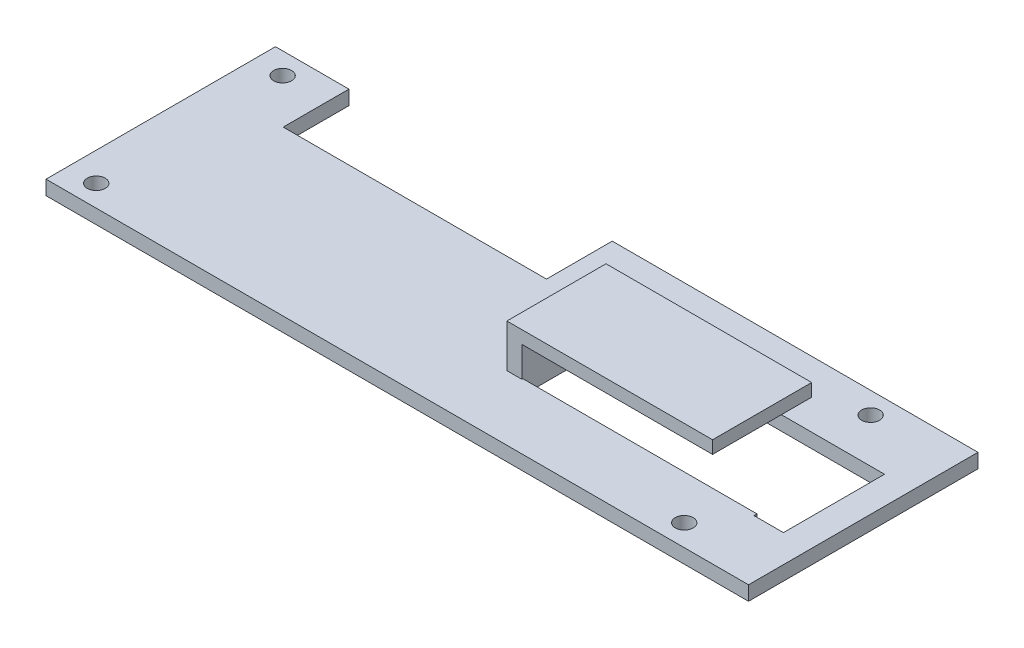
SolidWorks part; units mm, degrees
ref_plane "Front Plane" through (0, 0, 0) normal (0, 0, 1) x (1, 0, 0)
ref_plane "Top Plane" through (0, 0, 0) normal (0, 1, 0) x (1, 0, 0)
ref_plane "Right Plane" through (0, 0, 0) normal (1, 0, 0) x (0, 0, -1)
sketch "Sketch1" plane through (0, 0, 0) normal (0, 1, 0) x (1, 0, 0)
  line L1 (-57.15, -20.32) -> (57.15, -20.32)
  line L2 (-57.15, -20.32) -> (-57.15, 20.32)
  line L3 (-57.15, 20.32) -> (57.15, 20.32)
  line L4 (57.15, -20.32) -> (57.15, 20.32)
  line L5 (-57.15, -20.32) -> (57.15, 20.32) construction
  line L6 (-57.15, 20.32) -> (57.15, -20.32) construction
  point P0 (0, 0)
  dimension "D1" = 114.3
  dimension "D2" = 40.64
extrude "Boss-Extrude1" add sketch "Sketch1" along normal blind 2.54
sketch "Sketch2" plane through (0, 2.54, 0) normal (0, 1, 0) x (1, 0, 0)
  line L0 (57.15, 20.32) -> (-57.15, 20.32) construction
  line L1 (-57.15, -20.32) -> (57.15, -20.32) construction
  line L2 (-57.15, 20.32) -> (-57.15, -20.32) construction
  line L3 (57.15, -20.32) -> (57.15, 20.32) construction
  circle A0 centre (-52.07, 16.51) radius 1.5875
  circle A1 centre (52.07, 16.51) radius 1.5875
  circle A2 centre (52.07, -16.51) radius 1.5875
  circle A3 centre (-52.07, -16.51) radius 1.5875
  dimension "D1" = 3.175
  dimension "D2" = 3.81
  dimension "D3" = 3.81
  dimension "D4" = 3.81
  dimension "D5" = 3.81
  dimension "D6" = 5.08
  dimension "D7" = 5.08
  dimension "D8" = 5.08
  dimension "D9" = 5.08
extrude "Cut-Extrude2" cut sketch "Sketch2" against normal through all
sketch "Sketch3" plane through (0, 2.54, 0) normal (0, 1, 0) x (1, 0, 0)
  line L0 (57.15, 31.0755) -> (-57.15, 31.0755) construction
  line L1 (15.6834, -8.7) -> (58.8854, -8.7)
  line L2 (15.6834, -8.7) -> (15.6834, 8.6735)
  line L3 (15.6834, 8.6735) -> (58.8854, 8.6735)
  line L4 (58.8854, -8.7) -> (58.8854, 8.6735)
  line L5 (-44.1328, 8.6735) -> (2.4958, 8.6735)
  line L6 (-44.1328, 8.6735) -> (-44.1328, 31.0755)
  line L7 (-44.1328, 31.0755) -> (2.4958, 31.0755)
  line L8 (2.4958, 8.6735) -> (2.4958, 31.0755)
extrude "Cut-Extrude3" cut sketch "Sketch3" against normal through all
sketch "Sketch4" plane through (0, 2.54, 0) normal (0, 1, 0) x (1, 0, 0)
  line L1 (15.6834, 8.6735) -> (13.0397, 8.6735)
  line L2 (15.6834, 8.6735) -> (15.6834, -8.88)
  line L3 (15.6834, -8.88) -> (13.0397, -8.88)
  line L4 (13.0397, 8.6735) -> (13.0397, -8.88)
extrude "Boss-Extrude2" add sketch "Sketch4" along normal blind 7.62
sketch "Sketch5" plane through (15.6834, 0, 0) normal (1, 0, 0) x (0, 0, -1)
  line L0 (8.6735, 10.16) -> (8.6735, 2.54) construction
  line L1 (-8.88, 10.16) -> (8.6735, 10.16)
  line L2 (-8.88, 10.16) -> (-8.88, 7.9041)
  line L3 (-8.88, 7.9041) -> (8.6735, 7.9041)
  line L4 (8.6735, 10.16) -> (8.6735, 7.9041)
extrude "Boss-Extrude3" add sketch "Sketch5" along normal blind 33.782
sketch "Sketch6" plane through (0, 2.54, 0) normal (0, 1, 0) x (1, 0, 0)
  line L0 (57.15, 20.32) -> (57.15, 8.6735)
  line L1 (57.15, 8.6735) -> (62.366, 8.6735)
  line L2 (62.366, 8.6735) -> (62.366, -9.2307)
  line L3 (62.366, -9.2307) -> (57.15, -9.2307)
  line L4 (57.15, -36.8695) -> (57.15, 36.7905) construction
  line L5 (57.15, -9.2307) -> (57.15, -20.32)
  line L6 (57.15, -20.32) -> (67.2765, -20.32)
  line L7 (67.2765, -20.32) -> (67.2765, 20.32)
  line L8 (67.2765, 20.32) -> (57.15, 20.32)
extrude "Boss-Extrude4" add sketch "Sketch6" against normal blind 2.54
